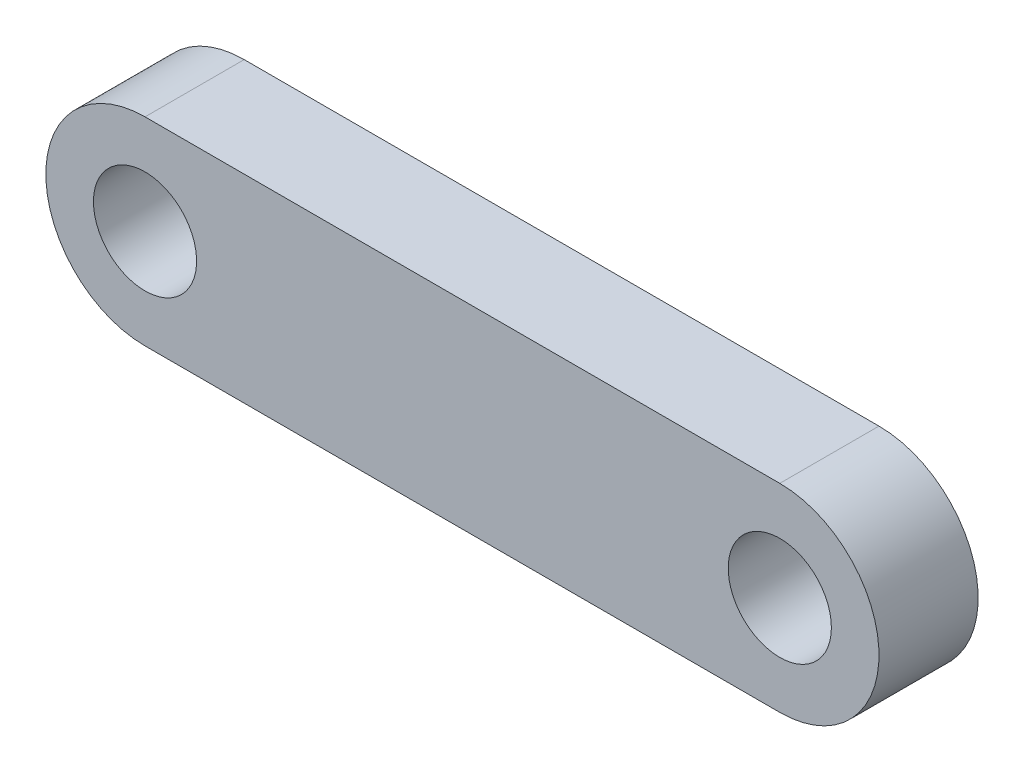
SolidWorks part; units mm, degrees
ref_plane "Front Plane" through (0, 0, 0) normal (0, 0, 1) x (1, 0, 0)
ref_plane "Top Plane" through (0, 0, 0) normal (0, 1, 0) x (1, 0, 0)
ref_plane "Right Plane" through (0, 0, 0) normal (1, 0, 0) x (0, 0, -1)
sketch "Sketch1" plane through (0, 0, 0) normal (0, 0, 1) x (1, 0, 0)
  line L1 (-71.1789, 3.175) -> (-50.8589, 3.175)
  line L2 (-61.0189, 3.175) -> (-61.0189, -2.7618) construction
  line L3 (-71.1789, -3.175) -> (-50.8589, -3.175)
  arc A0 (-50.8589, 3.175) -> (-50.8589, -3.175) centre (-50.8589, 0) cw
  arc A1 (-71.1789, 3.175) -> (-71.1789, -3.175) centre (-71.1789, 0) ccw
  circle A2 centre (-50.8589, 0) radius 1.651
  circle A3 centre (-71.1789, 0) radius 1.651
  dimension "D3" = 3.302
  dimension "D2" = 20.32
extrude "Boss-Extrude1" add sketch "Sketch1" along normal blind 3.175
